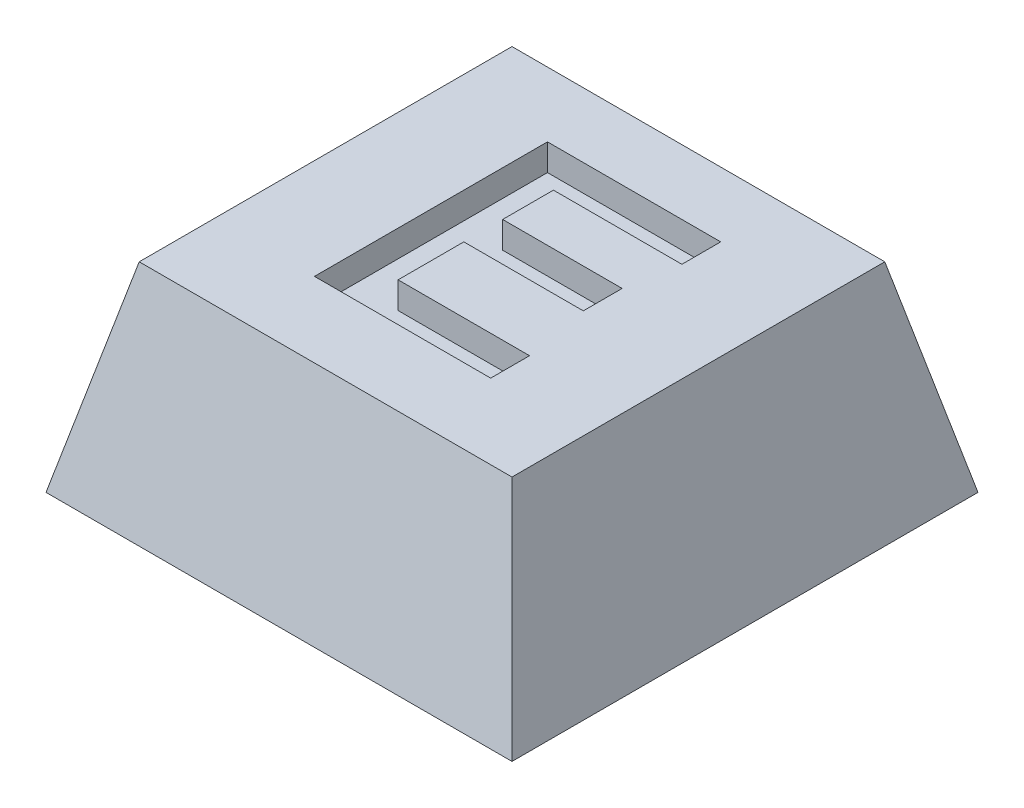
SolidWorks part; units mm, degrees
ref_plane "Front Plane" through (0, 0, 0) normal (0, 0, 1) x (1, 0, 0)
ref_plane "Top Plane" through (0, 0, 0) normal (0, 1, 0) x (1, 0, 0)
ref_plane "Right Plane" through (0, 0, 0) normal (1, 0, 0) x (0, 0, -1)
sketch "Sketch1" plane through (0, 0, 0) normal (0, 1, 0) x (1, 0, 0)
  line L1 (0, 0) -> (7, 0)
  line L2 (0, 0) -> (0, 7)
  line L3 (0, 7) -> (7, 7)
  line L4 (7, 0) -> (7, 7)
  dimension "D1" = 7
  dimension "D2" = 7
extrude "Boss-Extrude1" add sketch "Sketch1" along normal blind 3
sketch "Sketch2" plane through (0, 0, 0) normal (0, 0, 1) x (1, 0, 0)
  line L0 (0, 0) -> (0.7, 3)
  line L1 (0, 3) -> (7, 3) construction
  line L2 (0.7, 3) -> (0, 3)
  line L3 (0, 3) -> (0, 0)
  line L4 (7, 0) -> (6.3, 3)
  line L5 (6.3, 3) -> (7, 3)
  line L6 (7, 3) -> (7, 0)
  dimension "D1" = 0.7
  dimension "D2" = 0.7
extrude "Cut-Extrude1" cut sketch "Sketch2" against normal blind 7
sketch "Sketch3" plane through (0, 0, 0) normal (1, 0, 0) x (0, 0, -1)
  line L0 (0, 0) -> (0.7, 3)
  line L1 (7, 3) -> (0, 3) construction
  line L2 (0.7, 3) -> (0, 3)
  line L3 (0, 3) -> (0, 0)
  line L4 (7, 3) -> (6.3, 3)
  line L5 (6.3, 3) -> (7, 0)
  line L6 (7, 3) -> (7, 0)
  dimension "D1" = 0.7
  dimension "D2" = 0.7
extrude "Cut-Extrude2" cut sketch "Sketch3" along normal blind 11
sketch "Sketch4" plane through (0, 0, 0) normal (0, -1, 0) x (1, 0, 0)
  line L0 (3.5, 0) -> (3.5, -7) construction
  line L1 (0, 0) -> (7, 0) construction
  line L2 (7, -7) -> (0, -7) construction
  line L3 (0, -3.5) -> (7, -3.5) construction
  line L4 (0, -7) -> (0, 0) construction
  line L5 (7, 0) -> (7, -7) construction
  circle A0 centre (3.5, -3.5) radius 1.8
  dimension "D1" = 3.6
extrude "Cut-Extrude3" cut sketch "Sketch4" against normal blind 0.8
sketch "Sketch5" plane through (0, 3, 0) normal (0, 1, 0) x (1, 0, 0)
  text T0 "E" font "Arial" height 3.5
extrude "Cut-Extrude4" cut sketch "Sketch5" against normal blind 0.4
